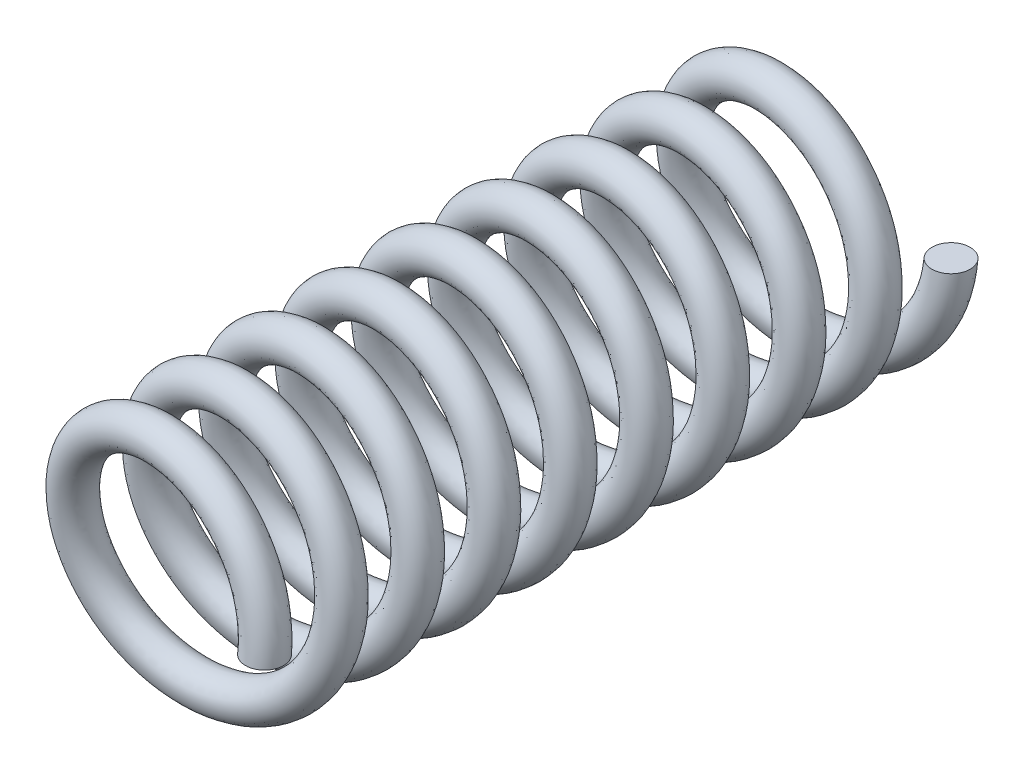
SolidWorks part; units mm, degrees
ref_plane "Front" through (0, 0, 0) normal (0, 0, 1) x (1, 0, 0)
ref_plane "Top" through (0, 0, 0) normal (0, 1, 0) x (1, 0, 0)
ref_plane "Right" through (0, 0, 0) normal (1, 0, 0) x (0, 0, -1)
sketch "草图1" plane through (0, 0, 0) normal (0, 0, 1) x (1, 0, 0)
  circle A0 centre (0, 0) radius 3
curve "螺旋线/涡状线1" pitch 2 height 18 turns 9
ref_plane "基准面1" through (0, 0, 0) normal (0, 1, 0) x (1, 0, 0)
sketch "草图5" plane through (0, 0, 0) normal (0, 1, 0) x (1, 0, 0)
  circle A0 centre (3.0051, 0) radius 0.5
sweep "扫描1" add profiles "草图5" path "螺旋线/涡状线1"
